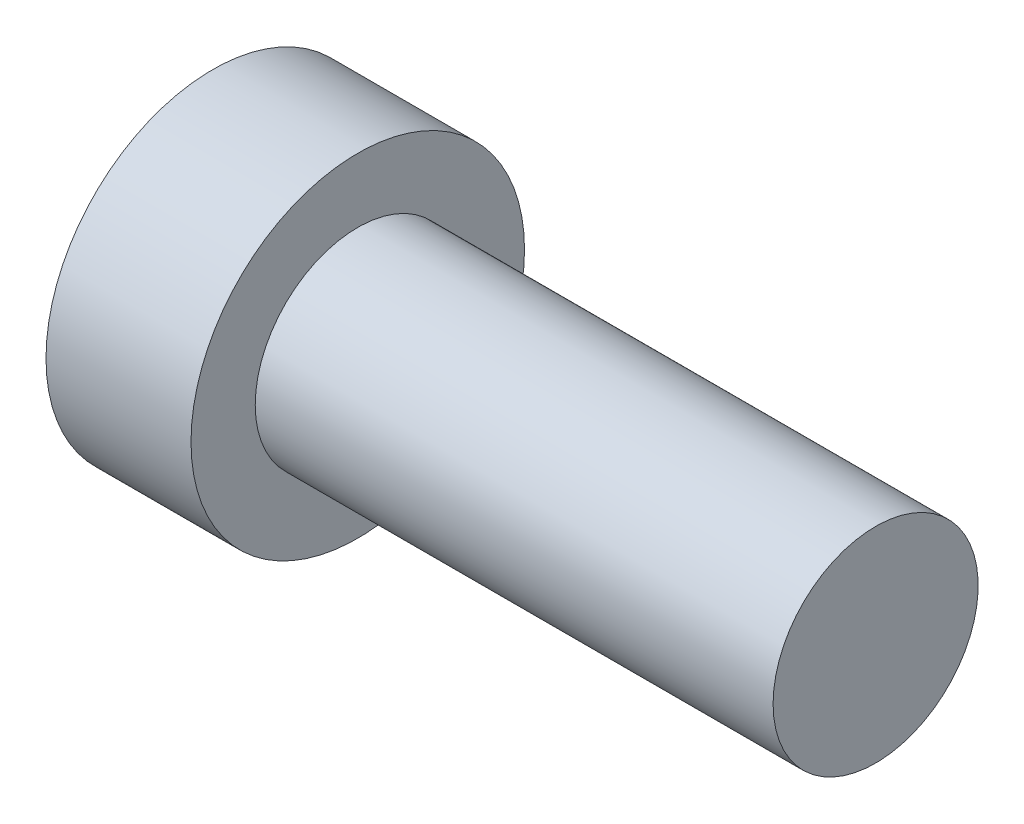
SolidWorks part; units mm, degrees
ref_plane "Plane1" through (0, 0, 0) normal (0, 0, 1) x (1, 0, 0)
ref_plane "Plane2" through (0, 0, 0) normal (0, 1, 0) x (1, 0, 0)
ref_plane "Plane3" through (0, 0, 0) normal (1, 0, 0) x (0, 0, -1)
sketch "BodySke" plane through (0, 0, 0) normal (0, 0, 1) x (1, 0, 0)
  line L0 (2.413, 1.2573) -> (2.413, 2.0447)
  line L1 (2.413, 2.0447) -> (0.635, 2.0447)
  line L2 (-25.4, 0) -> (127, 0) construction
  line L3 (8.763, 0) -> (0, 0)
  line L4 (2.413, 1.2573) -> (8.763, 1.2573)
  line L5 (8.763, 1.2573) -> (8.763, 0)
  line L6 (2.413, -2.0447) -> (0.635, -2.0447) construction
  line L7 (2.413, -1.2573) -> (8.763, -1.2573) construction
  line L8 (2.9413, 1.2192) -> (2.9413, -0.4698) construction
  line L9 (2.413, 1.2192) -> (2.413, -0.4698) construction
  arc A0 (0, 0) -> (0.635, 2.0447) centre (3.6095, 0) cw
  dimension "Head_ht" = 2.413
  dimension "Diameter" = 2.5146
  dimension "Length" = 6.35
  dimension "Head_dia" = 4.0894
  dimension "Head_side_ht" = 1.778
  dimension "Advance" = 0.5283
  dimension "Thread_nom" = 6.35
revolve "Base-Revolve" add sketch "BodySke" angle 360 about L2
cosmetic thread "ThreadCosmetic" [suppressed] parameters "Thread_length"=5.8217, "Thread_minor"=1.8821
sketch "Sketch2" plane through (0, 0, 0) normal (1, 0, 0) x (0, 0, -1)
  line L0 (-2.0447, -0.4445) -> (-2.0447, 0.4445)
  line L1 (-2.0447, 0.4445) -> (2.0447, 0.4445)
  line L2 (2.0447, 0.4445) -> (2.0447, -0.4445)
  line L3 (2.0447, -0.4445) -> (-2.0447, -0.4445)
  dimension "D1" = 4.0894
  dimension "D2" = 2.0447
  dimension "D3" = 0.4445
  dimension "Slot_width" = 0.889
extrude "Slot" [suppressed] cut sketch "Sketch2" along normal blind 1.0922
sketch "Sketch3" plane through (0, 0, 0) normal (1, 0, 0) x (0, 0, -1)
  line L0 (0.3429, -1.5367) -> (-0.3429, -1.5367)
  line L1 (0.3429, -1.5367) -> (0.3429, 1.5367)
  line L2 (-0.3429, 1.5367) -> (0.3429, 1.5367)
  line L3 (-0.3429, 1.5367) -> (-0.3429, -1.5367)
  dimension "D1" = 0.3429
  dimension "Cross_width" = 0.6858
  dimension "D2" = 1.5367
  dimension "Cross_dia" = 3.0734
ref_plane "Plane4" through (1.7018, 0, 0) normal (1, 0, 0) x (0, 0, -1)
sketch "Sketch4" plane through (1.7018, 0, 0) normal (1, 0, 0) x (0, 0, -1)
  line L0 (0.1715, -0.1714) -> (-0.1714, -0.1715)
  line L1 (0.1715, -0.1714) -> (0.1715, 0.1714)
  line L2 (-0.1715, 0.1714) -> (0.1715, 0.1714)
  line L3 (-0.1715, 0.1714) -> (-0.1714, -0.1715)
  dimension "D1" = 0.3429
  dimension "D2" = 0.1714
  dimension "D3" = 0.3429
  dimension "D4" = 0.1714
loft "Cross" cut profiles "Sketch3", "Sketch4"
pattern_circular "CirPattern1" count 2 every 90 about axis through (0, 0, 0) along (1, 0, 0) of "Cross"
sketch "Sketch5" plane through (0, 0, 0) normal (0, 1, 0) x (1, 0, 0)
  line L4 (-25.4, 0) -> (127, 0) construction
  line L5 (2.413, -6.312) -> (2.413, 6.3337) construction
  circle A0 centre (1.651, 0) radius 0.4699
  dimension "Drilled_hole_dia" = 0.9398
  dimension "D1" = 2.413
  dimension "Drilled_hole_loc" = 0.762
extrude "Hole" [suppressed] cut sketch "Sketch5" against normal through all and the other way through all
sketch "ThdSchSke" plane through (0, 0, 0) normal (0, 0, 1) x (1, 0, 0)
  line L0 (2.9413, -0.9411) -> (2.7199, -1.2573)
  line L1 (2.9413, -0.9411) -> (3.1627, -1.2573)
  line L2 (3.1627, -1.2573) -> (3.1627, -1.5716)
  line L3 (-3.175, 0) -> (5.1513, 0) construction
  line L5 (3.1627, -1.5716) -> (2.7199, -1.5716)
  line L6 (2.7199, -1.5716) -> (2.7199, -1.2573)
  dimension "Thread_minor" = 1.8821
  dimension "Diameter" = 2.5146
  dimension "Start" = 2.9413
  dimension "SideAngle" = 55
  dimension "VeeAngle" = 70
  dimension "Overcut" = 3.1432
revolve "ThreadSchematic" [suppressed] cut sketch "ThdSchSke" angle 360 about L3
pattern_linear "ThdSchPat" [suppressed]
equation "\"D1@Sketch3\" = \"Cross_width@Sketch3\" / 2"
equation "\"D2@Sketch3\" = \"Cross_dia@Sketch3\" / 2"
equation "\"D1@Sketch4\" = \"Cross_width@Sketch3\"*.5"
equation "\"D2@Sketch4\" = \"D1@Sketch4\" / 2"
equation "\"D3@Sketch4\" = \"D1@Sketch4\""
equation "\"D4@Sketch4\" = \"D2@Sketch4\""
equation "\"D1@Sketch2\" = \"Head_dia@BodySke\""
equation "\"D2@Sketch2\" = \"D1@Sketch2\" / 2"
equation "\"D3@Sketch2\" = \"Slot_width@Sketch2\" / 2"
equation "\"D1@Sketch5\" = \"Head_ht@BodySke\""
equation "\"Thread_length@ThreadCosmetic\" = ((sgn( (\"Length@BodySke\" - \"Advance@BodySke\" ) - \"Thread_nom@BodySke\" )-1)*( (\"Length@BodySke\" - \"Advance@BodySke\" ) - \"Thread_nom@BodySke\" ))/-2+ \"Thread_nom@BodySke\""
equation "\"Thread_minor@ThdSchSke\" = \"Thread_minor@ThreadCosmetic\""
equation "\"Diameter@ThdSchSke\" = \"Diameter@BodySke\""
equation "\"Overcut@ThdSchSke\" = \"Diameter@BodySke\" * 1.25"
equation "\"Start@ThdSchSke\" = \"Head_ht@BodySke\" + \"Length@BodySke\" - \"Thread_length@ThreadCosmetic\"  '---Non-countersunk---"
equation "\"Num_threads@ThdSchPat\" = int( \"Thread_length@ThreadCosmetic\" / \"Advance@BodySke\" + 0.999 )  + 1"
equation "\"Advance@ThdSchPat\" = \"Thread_length@ThreadCosmetic\" /  (\"Num_threads@ThdSchPat\" - 1) 'relax it"
